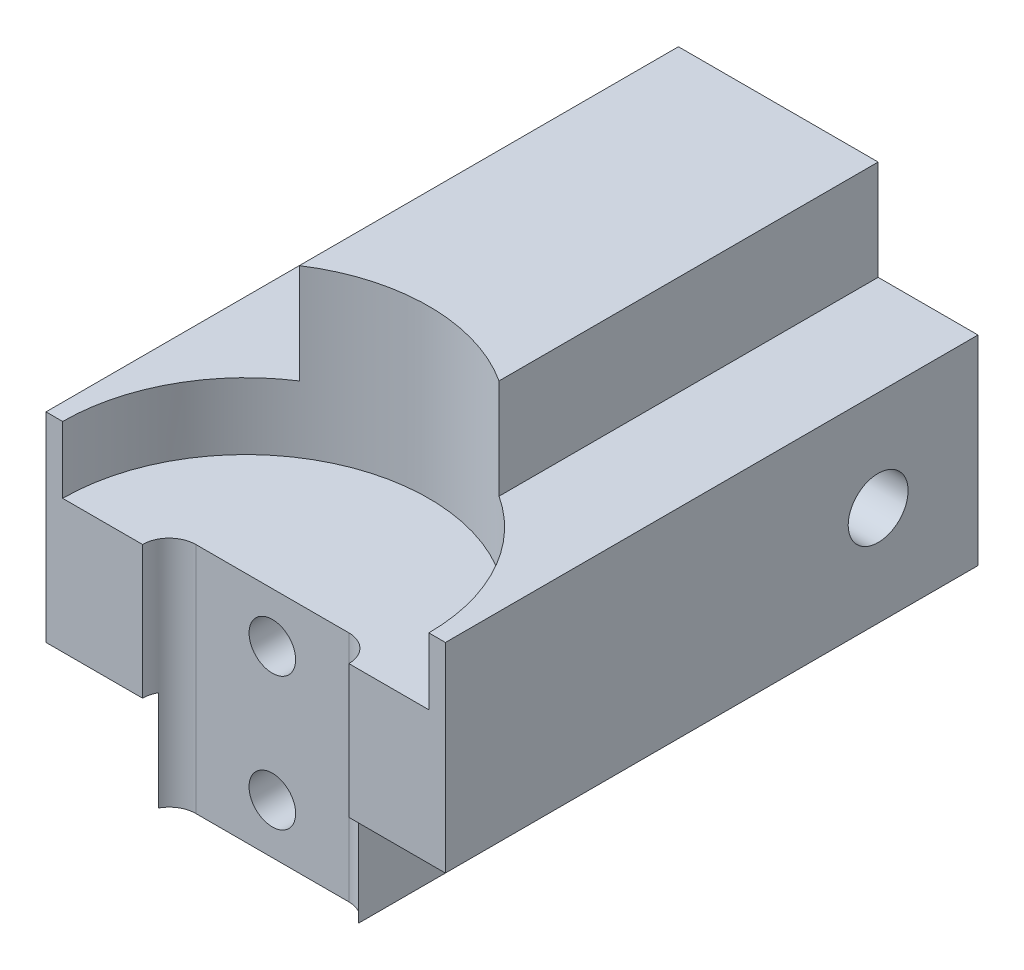
SolidWorks part; units mm, degrees
ref_plane "Piano frontale" through (0, 0, 0) normal (0, 0, 1) x (1, 0, 0)
ref_plane "Piano superiore" through (0, 0, 0) normal (0, 1, 0) x (1, 0, 0)
ref_plane "Piano destro" through (0, 0, 0) normal (1, 0, 0) x (0, 0, -1)
sketch "Schizzo1" plane through (0, 0, 0) normal (0, 0, 1) x (1, 0, 0)
  line L0 (0, 112.8068) -> (0, -95.5607) construction
  line L1 (-75.0941, 0) -> (126.8367, 0) construction
  line L2 (-30, 60) -> (30, 60)
  line L3 (30, 60) -> (30, 30)
  line L4 (30, 30) -> (60, 30)
  line L5 (60, 30) -> (60, -30)
  line L6 (30, -30) -> (60, -30)
  line L7 (30, -60) -> (30, -30)
  line L8 (-30, -60) -> (30, -60)
  line L9 (-30, -60) -> (-30, -30)
  line L10 (-30, -30) -> (-60, -30)
  line L11 (-60, 30) -> (-60, -30)
  line L12 (-30, 30) -> (-60, 30)
  line L13 (-30, 60) -> (-30, 30)
  point P11 (60, 0)
  point P14 (0, 0)
  point P16 (0, -60)
  point P21 (0, 60)
  dimension "D1" = 60
  dimension "D2" = 60
  dimension "D3" = 30
  dimension "D4" = 120
extrude "Estrusione-Estrusione1" add sketch "Schizzo1" along normal mid plane 160
sketch "Schizzo2" plane through (0, 60, 0) normal (0, 1, 0) x (1, 0, 0)
  line L1 (30, -80) -> (-30, -80) construction
  circle A0 centre (0, -80) radius 55
  dimension "D1" = 110
extrude "Taglio-Estrusione1" cut sketch "Schizzo2" against normal blind 50
sketch "Schizzo3" plane through (0, 10, 0) normal (0, 1, 0) x (1, 0, 0)
  line L0 (-23, -80) -> (23, -80) construction
  line L1 (55, -80) -> (-55, -80) construction
  line L2 (-23, -72) -> (23, -72)
  line L3 (-23, -88) -> (23, -88)
  line L4 (0, 0) -> (0, -116.0155) construction
  arc A0 (-23, -72) -> (-23, -88) centre (-23, -80) ccw
  arc A1 (23, -88) -> (23, -72) centre (23, -80) ccw
  point P4 (0, -80)
  point P12 (0, 0)
  dimension "D2" = 8
  dimension "D1" = 46
extrude "Taglio-Estrusione2" cut sketch "Schizzo3" against normal up to next
hole_wizard "Foro Ø18.0 (18)-1" positions "Schizzo4" profile "Schizzo5" hole size "Ø18.0" standard "ISO" end condition through all
sketch "Schizzo4" plane through (-60, 0, 0) normal (-1, 0, 0) x (0, 0, 1)
  line L1 (0, 0) -> (-109.8311, 0) construction
  line L2 (-80, 30) -> (-80, -30) construction
  point P10 (-50, 0)
  dimension "D1" = 30
sketch "Schizzo5" plane through (-60, 0, -50) normal (0, 1, 0) x (0, 0, 1)
  line L0 (0, 0) -> (0, 120)
  line L1 (0, 120) -> (9, 120)
  line L2 (9, 120) -> (9, 0)
  line L5 (9, 0) -> (0, 0)
  line L11 (0, -6.35) -> (0, 107.95) construction
  dimension "Thru Hole Dia." = 18
  dimension "Thru Hole Depth" = 120
hole_wizard "Foro filettato M22-1" positions "Schizzo6" profile "Schizzo7" tap size "M22" standard "ISO"
sketch "Schizzo6" plane through (0, 0, -80) normal (0, 0, -1) x (-1, 0, 0)
  point P0 (0, 0)
sketch "Schizzo7" plane through (0, 0, -80) normal (1, 0, 0) x (0, 1, 0)
  line L0 (0, 0) -> (0, 65.8584)
  line L1 (0, 65.8584) -> (9.75, 60)
  line L2 (9.75, 60) -> (9.75, 0)
  line L5 (9.75, 0) -> (0, 0)
  line L10 (0, 65.8584) -> (-9.75, 60) construction
  line L11 (0, -6.35) -> (0, 107.95) construction
  dimension "Tap Drill Dia." = 19.5
  dimension "Tap Drill Depth" = 60
  dimension "Drill Angle" = 118
cosmetic thread "Filettatura del foro1" parameters "D1"=45, "D2"=22
hole_wizard "Foro filettato M16-1" positions "Schizzo8" profile "Schizzo9" tap size "M16" standard "ISO"
sketch "Schizzo8" plane through (0, 0, 72) normal (0, 0, 1) x (1, 0, 0)
  line L0 (23, 10) -> (-23, 10) construction
  point P0 (0, -5)
  point P2 (0, -45)
  dimension "D1" = 40
  dimension "D2" = 15
sketch "Schizzo9" plane through (0, -5, 72) normal (1, 0, 0) x (0, -1, 0)
  line L0 (0, 0) -> (0, 39.206)
  line L1 (0, 39.206) -> (7, 35)
  line L2 (7, 35) -> (7, 0)
  line L5 (7, 0) -> (0, 0)
  line L10 (0, 39.206) -> (-7, 35) construction
  line L11 (0, -6.35) -> (0, 107.95) construction
  dimension "Tap Drill Dia." = 14
  dimension "Tap Drill Depth" = 35
  dimension "Drill Angle" = 118
cosmetic thread "Filettatura del foro2" parameters "D1"=28, "D2"=16
cosmetic thread "Filettatura del foro3" parameters "D1"=28, "D2"=16
sketch "Schizzo10" plane through (0, -60, 0) normal (0, -1, 0) x (1, 0, 0)
  line L0 (0, 0) -> (93.9381, 0)
